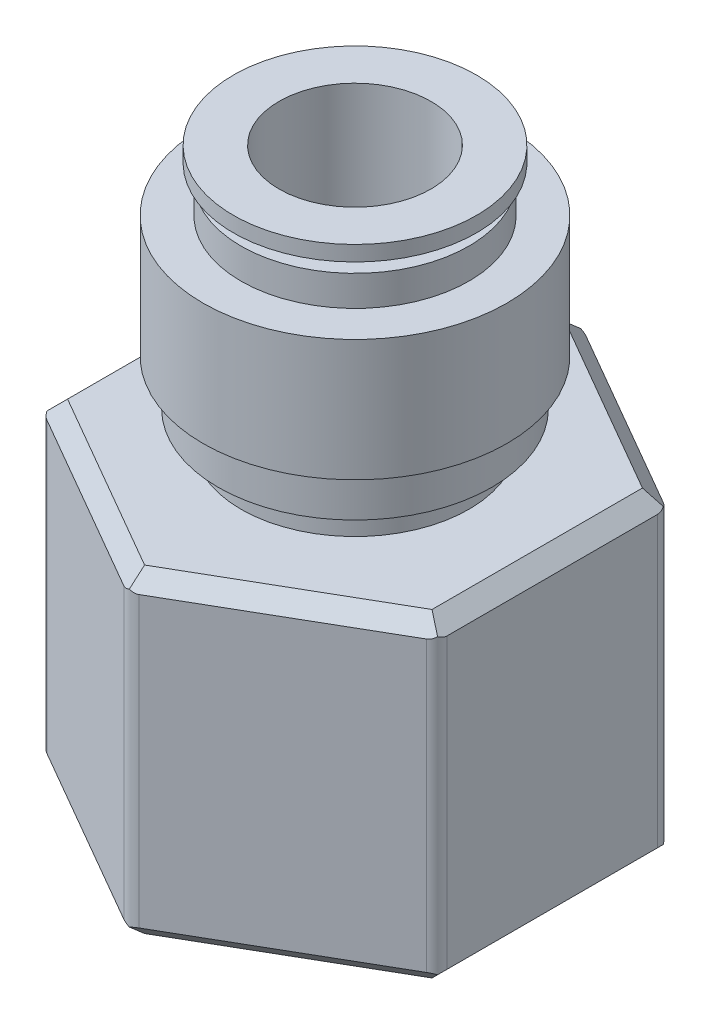
SolidWorks part; units mm, degrees
ref_plane "Спереди" through (0, 0, 0) normal (0, 0, 1) x (1, 0, 0)
ref_plane "Сверху" through (0, 0, 0) normal (0, 1, 0) x (1, 0, 0)
ref_plane "Справа" through (0, 0, 0) normal (1, 0, 0) x (0, 0, -1)
sketch "Эскиз1" plane through (0, 0, 0) normal (0, 1, 0) x (1, 0, 0)
  line L1 (0, 15) -> (-12.9904, 7.5)
  line L2 (-12.9904, 7.5) -> (-12.9904, -7.5)
  line L3 (-12.9904, -7.5) -> (0, -15)
  line L4 (0, -15) -> (12.9904, -7.5)
  line L5 (12.9904, -7.5) -> (12.9904, 7.5)
  line L6 (12.9904, 7.5) -> (0, 15)
  circle A0 centre (0, 0) radius 12.9904 construction
  circle A1 centre (0, 0) radius 15 construction
  dimension "D1" = 30
extrude "Бобышка-Вытянуть1" add sketch "Эскиз1" along normal blind 21
sketch "Эскиз2" plane through (0, 21, 0) normal (0, 1, 0) x (1, 0, 0)
  circle A0 centre (0, 0) radius 7.5
  dimension "D1" = 15
extrude "Бобышка-Вытянуть2" add sketch "Эскиз2" along normal blind 2
sketch "Эскиз3" plane through (0, 23, 0) normal (0, 1, 0) x (1, 0, 0)
  circle A0 centre (0, 0) radius 9
  dimension "D1" = 18
extrude "Бобышка-Вытянуть3" add sketch "Эскиз3" along normal blind 3
sketch "Эскиз4" plane through (0, 26, 0) normal (0, 1, 0) x (1, 0, 0)
  circle A0 centre (0, 0) radius 10
  dimension "D1" = 20
extrude "Бобышка-Вытянуть4" add sketch "Эскиз4" along normal blind 8
sketch "Эскиз5" plane through (0, 34, 0) normal (0, 1, 0) x (1, 0, 0)
  circle A0 centre (0, 0) radius 7.5
  dimension "D1" = 15
extrude "Бобышка-Вытянуть5" add sketch "Эскиз5" along normal blind 2
sketch "Эскиз6" plane through (0, 0, 0) normal (0, 0, 1) x (1, 0, 0)
  line L0 (-8, 37) -> (-6, 37)
  line L1 (-4, 38) -> (-8, 38)
  line L2 (-8, 38) -> (-8, 37)
  line L9 (-4, 38) -> (-4, 36)
  line L10 (-6, 37) -> (-6, 36)
  line L11 (0, 36) -> (0, 38.2854) construction
  line L13 (7.5, 36) -> (-7.5, 36) construction
  line L14 (-6, 36) -> (-4, 36)
revolve "Повернуть1" add sketch "Эскиз6" angle 360 about L11
sketch "Эскиз7" plane through (0, 36, 0) normal (0, 1, 0) x (1, 0, 0)
  circle A0 centre (0, 0) radius 4
extrude "Вырез-Вытянуть1" cut sketch "Эскиз7" against normal through all and the other way through all
hole_wizard "Отверстие обработанное метчиком G1/21" positions "Эскиз8" profile "Эскиз9" tap size "G1/2" standard "ISO"
sketch "Эскиз8" plane through (0, 0, 0) normal (0, -1, 0) x (-1, 0, 0)
  point P0 (0, 0)
sketch "Эскиз9" plane through (0, 0, 0) normal (1, 0, 0) x (0, 0, -1)
  line L0 (0, 0) -> (0, 23.7082)
  line L1 (0, 23.7082) -> (9.5, 18)
  line L2 (9.5, 18) -> (9.5, 0)
  line L5 (9.5, 0) -> (0, 0)
  line L10 (0, 23.7082) -> (-9.5, 18) construction
  line L11 (0, -6.35) -> (0, 107.95) construction
  dimension "Диаметр сверла" = 19
  dimension "Глубина сверла" = 18
  dimension "Угол заточки сверла" = 118
cosmetic thread "Отверстие резьбы1" parameters "D1"=18, "D2"=20.955
chamfer "Фаска1" distance 1 angle 45 13 edges at (12.9904, 21, 0) (6.4952, 21, 11.25) (-6.4952, 21, 11.25) (-12.9904, 21, 0) (-6.4952, 21, -11.25) (6.4952, 21, -11.25) (0, 0, -9.5) (-6.4952, 0, -11.25) (-12.9904, 0, 0) (-6.4952, 0, 11.25) (6.4952, 0, 11.25) (12.9904, 0, 0) (6.4952, 0, -11.25)
fillet "Скругление1" radius 1 6 edges at (12.9904, 10.5, 7.5) (0, 10.5, 15) (-12.9904, 10.5, 7.5) (-12.9904, 10.5, -7.5) (0, 10.5, -15) (12.9904, 10.5, -7.5)
sketch "Эскиз10" plane through (0, 38, 0) normal (0, 1, 0) x (1, 0, 0)
  circle A0 centre (0, 0) radius 5
  dimension "D1" = 10
extrude "Вырез-Вытянуть2" cut sketch "Эскиз10" against normal blind 40
